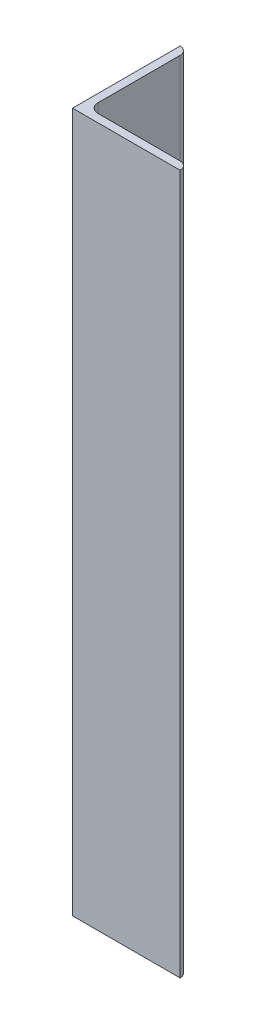
SolidWorks part; units mm, degrees
ref_plane "Front Plane" through (0, 0, 0) normal (0, 0, 1) x (1, 0, 0)
ref_plane "Top Plane" through (0, 0, 0) normal (0, 1, 0) x (1, 0, 0)
ref_plane "Right Plane" through (0, 0, 0) normal (1, 0, 0) x (0, 0, -1)
sketch3d "3DSketch1"
  line L0 (0, 0, 0) -> (0, 260, 0)
  dimension "D1" = 260
other "Iron V40X40X3(1)"
ref_plane "Plane1" through (0, 0, 0) normal (0, 1, 0) x (1, 0, 0)
sketch "Sketch1" plane through (0, 0, 0) normal (0, 1, 0) x (1, 0, 0)
  line L0 (0, 0) -> (0, 40)
  line L1 (0, 20) -> (3, 20) construction
  line L2 (3, 37) -> (3, 6.5)
  line L3 (6.5, 3) -> (37, 3)
  line L4 (20, 3) -> (20, 0) construction
  line L5 (40, 0) -> (0, 0)
  arc A0 (40, 0) -> (37, 3) centre (37, 0) ccw
  arc A1 (0, 40) -> (3, 37) centre (0, 37) cw
  arc A2 (6.5, 3) -> (3, 6.5) centre (6.5, 6.5) cw
  point P10 (20, 0)
  point P14 (0, 20)
  point P15 (3, 20)
  point P16 (20, 3)
  point P17 (3, 40)
  point P18 (40, 3)
  point P21 (0, 0)
  dimension "D2" = 3
  dimension "D3" = 40
  dimension "Radius_1" = 3.5
  dimension "D1" = 3
sketch "Sketch2" plane through (0, 0, 0) normal (1, 0, 0) x (0, 0, -1)
  line L0 (10.5, 50) -> (25.5, 50) construction
  line L1 (10.5, 55) -> (25.5, 55)
  line L2 (10.5, 45) -> (25.5, 45)
  line L4 (0, 0) -> (0, 260) construction
  line L5 (10.5, 80) -> (25.5, 80) construction
  line L6 (10.5, 85) -> (25.5, 85)
  line L7 (10.5, 75) -> (25.5, 75)
  line L14 (40, 0) -> (0, 0) construction
  arc A0 (10.5, 55) -> (10.5, 45) centre (10.5, 50) ccw
  arc A1 (25.5, 45) -> (25.5, 55) centre (25.5, 50) ccw
  arc A2 (10.5, 85) -> (10.5, 75) centre (10.5, 80) ccw
  arc A3 (25.5, 75) -> (25.5, 85) centre (25.5, 80) ccw
  point P2 (18, 50)
  point P14 (18, 80)
  dimension "D2" = 5
  dimension "D1" = 15
  dimension "D3" = 50
  dimension "D4" = 18
  dimension "D5" = 2
extrude "Cut-Extrude1" cut sketch "Sketch2" along normal blind 10
